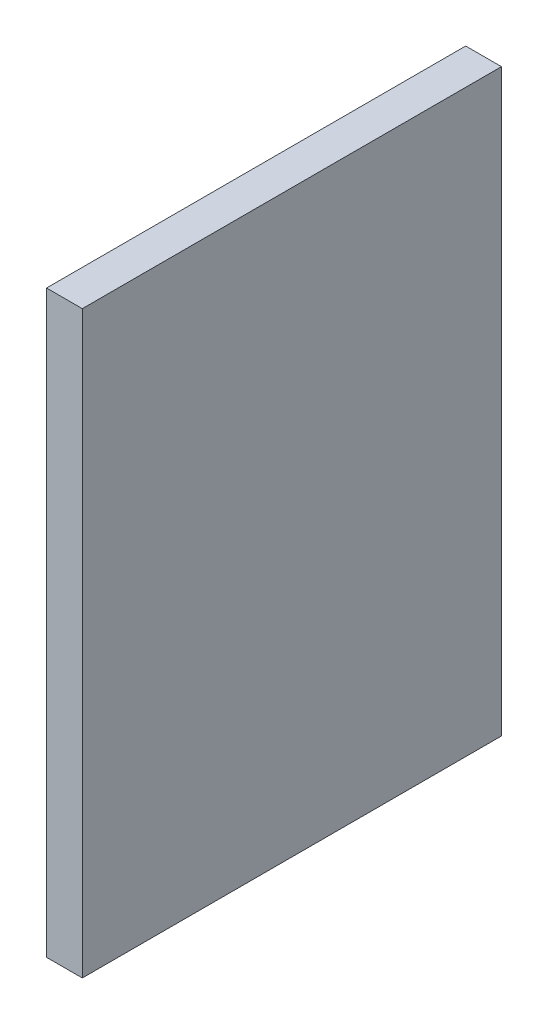
SolidWorks part; units mm, degrees
ref_plane "前视基准面" through (0, 0, 0) normal (0, 0, 1) x (1, 0, 0)
ref_plane "上视基准面" through (0, 0, 0) normal (0, 1, 0) x (1, 0, 0)
ref_plane "右视基准面" through (0, 0, 0) normal (1, 0, 0) x (0, 0, -1)
other "Configuration Table"
sketch "草图1" plane through (0, 0, 0) normal (1, 0, 0) x (0, 0, -1)
  line L1 (-25.2, 34.85) -> (25.2, 34.85)
  line L2 (-25.2, 34.85) -> (-25.2, -34.85)
  line L3 (-25.2, -34.85) -> (25.2, -34.85)
  line L4 (25.2, 34.85) -> (25.2, -34.85)
  line L5 (-25.2, 34.85) -> (25.2, -34.85) construction
  line L6 (-25.2, -34.85) -> (25.2, 34.85) construction
  point P0 (0, 0)
  dimension "D1" = 50.4
  dimension "D2" = 69.7
extrude "凸台-拉伸1" add sketch "草图1" along normal blind 4.3
